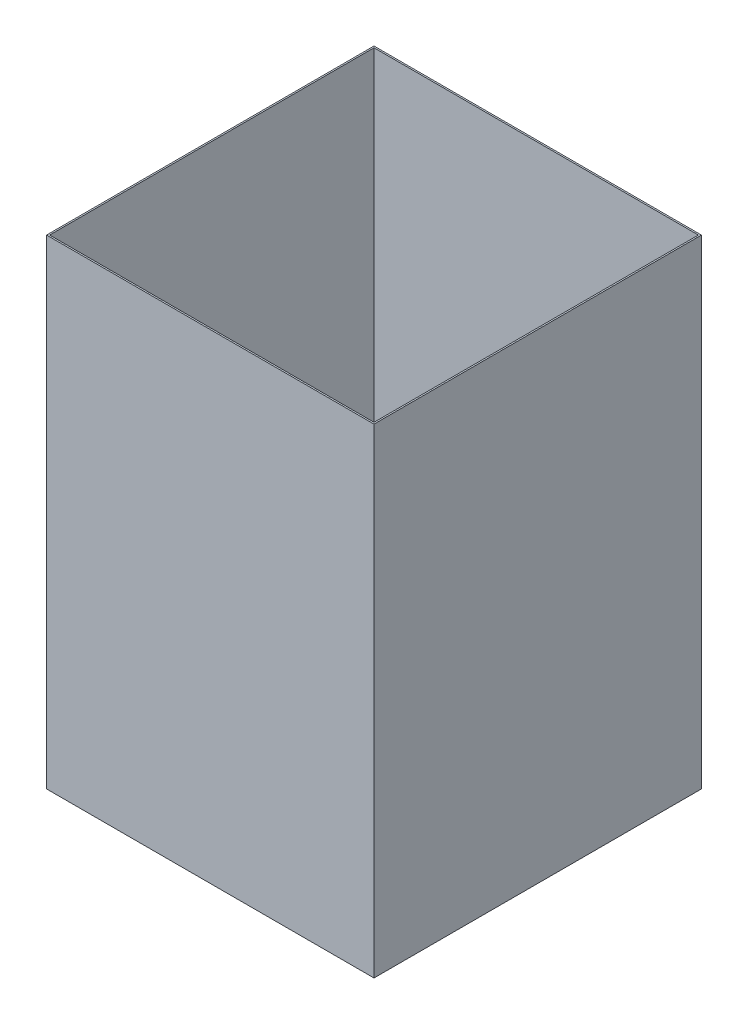
SolidWorks part; units mm, degrees
material "6061 Alloy"
ref_plane "Front Plane" through (0, 0, 0) normal (0, 0, 1) x (1, 0, 0)
ref_plane "Top Plane" through (0, 0, 0) normal (0, 1, 0) x (1, 0, 0)
ref_plane "Right Plane" through (0, 0, 0) normal (1, 0, 0) x (0, 0, -1)
sketch "Sketch1" plane through (0, 0, 0) normal (0, 1, 0) x (1, 0, 0)
  line L1 (-215, -215) -> (215, -215)
  line L2 (-215, -215) -> (-215, 215)
  line L3 (-215, 215) -> (215, 215)
  line L4 (215, -215) -> (215, 215)
  line L5 (-215, -215) -> (215, 215) construction
  line L6 (-215, 215) -> (215, -215) construction
  point P0 (0, 0)
extrude "Boss-Extrude1" add sketch "Sketch1" along normal blind 630
shell "Shell1" thickness 2
